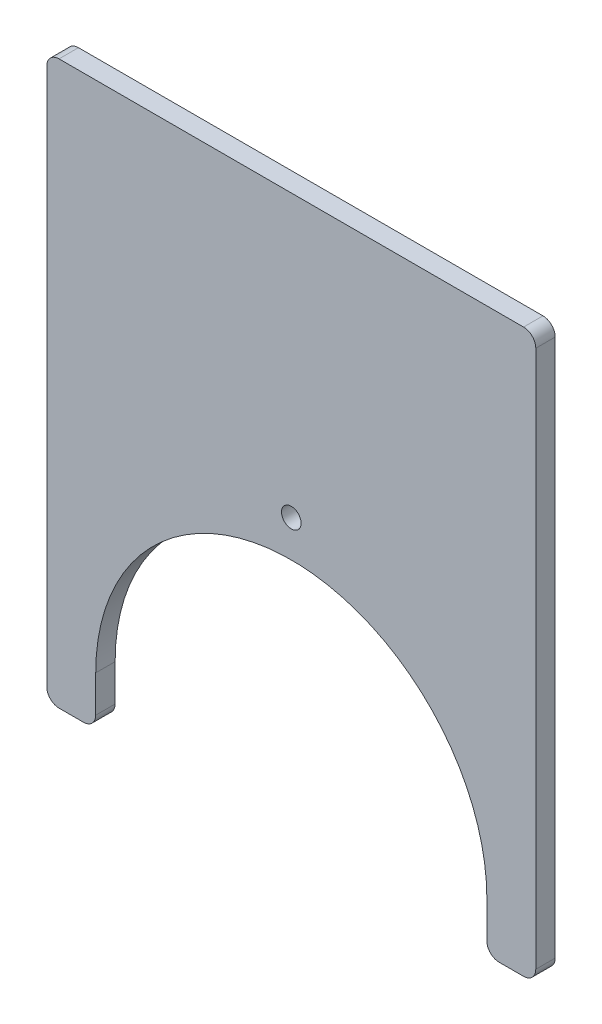
SolidWorks part; units mm, degrees
ref_plane "Front Plane" through (0, 0, 0) normal (0, 0, 1) x (1, 0, 0)
ref_plane "Top Plane" through (0, 0, 0) normal (0, 1, 0) x (1, 0, 0)
ref_plane "Right Plane" through (0, 0, 0) normal (1, 0, 0) x (0, 0, -1)
sketch "Sketch1" plane through (0, 0, 0) normal (0, 0, 1) x (1, 0, 0)
  line L1 (-200, 230) -> (200, 230)
  line L2 (-200, 230) -> (-200, -230)
  line L3 (-200, -230) -> (200, -230)
  line L4 (200, 230) -> (200, -230)
  line L5 (-200, 230) -> (200, -230) construction
  line L6 (-200, -230) -> (200, 230) construction
  point P0 (0, 0)
  dimension "D1" = 400
  dimension "D2" = 460
extrude "Boss-Extrude1" add sketch "Sketch1" against normal blind 15.875
sketch "Sketch2" plane through (0, 0, 0) normal (0, 0, 1) x (1, 0, 0)
  line L0 (160, -230) -> (160, -190)
  line L1 (-200, -230) -> (200, -230) construction
  line L2 (-160, -230) -> (-160, -190)
  line L3 (-160, -230) -> (160, -230)
  line L4 (200, -230) -> (200, 230) construction
  arc A0 (160, -190) -> (-160, -190) centre (0, -190) ccw
  dimension "D2" = 40
  dimension "D1" = 40
extrude "Cut-Extrude1" cut sketch "Sketch2" against normal through all
fillet "Fillet1" radius 10 6 edges at (-160, -230, -7.9375) (-200, -230, -7.9375) (160, -230, -7.9375) (200, -230, -7.9375) (-200, 230, -7.9375) (200, 230, -7.9375)
sketch "Sketch3" plane through (0, 0, 0) normal (0, 0, 1) x (1, 0, 0)
  line L0 (190, 230) -> (-190, 230) construction
  circle A0 centre (0, 0) radius 8
  dimension "D2" = 16
  dimension "D1" = 230
extrude "Cut-Extrude2" cut sketch "Sketch3" against normal through all
